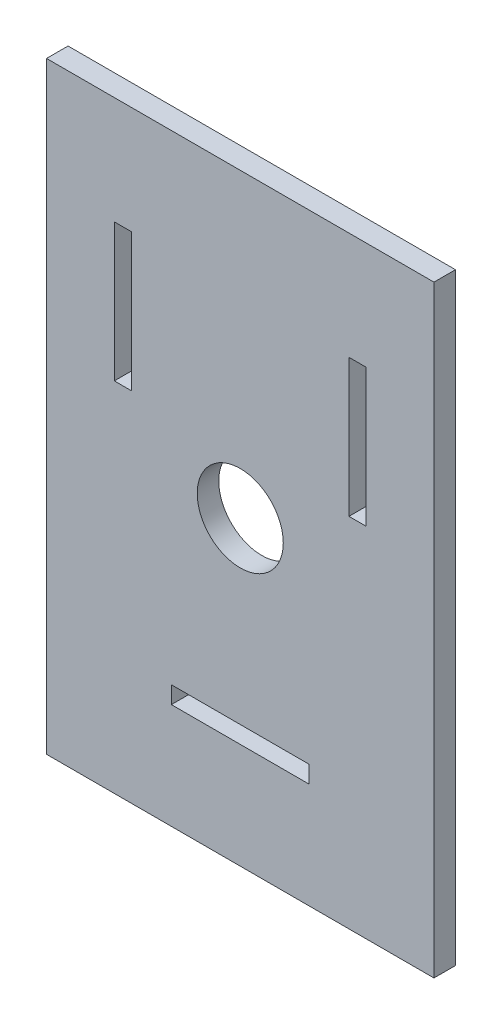
SolidWorks part; units mm, degrees
material "Alloy Steel"
ref_plane "Front Plane" through (0, 0, 0) normal (0, 0, 1) x (1, 0, 0)
ref_plane "Top Plane" through (0, 0, 0) normal (0, 1, 0) x (1, 0, 0)
ref_plane "Right Plane" through (0, 0, 0) normal (1, 0, 0) x (0, 0, -1)
sketch "BaseS" plane through (0, 0, 0) normal (0, 0, 1) x (1, 0, 0)
  line L1 (-9, 14) -> (9, 14)
  line L2 (-9, 14) -> (-9, -14)
  line L3 (-9, -14) -> (9, -14)
  line L4 (9, 14) -> (9, -14)
  line L5 (-9, 14) -> (9, -14) construction
  line L6 (-9, -14) -> (9, 14) construction
  point P0 (0, 0)
  dimension "Width" = 18
  dimension "Length" = 28
extrude "BASE" add sketch "BaseS" against normal blind 1
sketch "NeutralS" plane through (0, 0, 0) normal (0, 0, 1) x (1, 0, 0)
  line L1 (5.05, 9) -> (5.85, 9)
  line L2 (5.05, 9) -> (5.05, 2.6)
  line L3 (5.05, 2.6) -> (5.85, 2.6)
  line L4 (5.85, 9) -> (5.85, 2.6)
  line L5 (5.05, 9) -> (5.85, 2.6) construction
  line L6 (5.05, 2.6) -> (5.85, 9) construction
  point P0 (5.45, 5.8)
  dimension "Height" = 6.4
  dimension "Width" = 0.8
  dimension "XLoc" = 5.45
  dimension "YLoc" = 5.8
extrude "NEUTRAL" cut sketch "NeutralS" against normal blind 1.6
mirror "LINE HM" about plane through (0, 0, 0) normal (1, 0, 0) of "NEUTRAL"
sketch "ScrewAccessS" plane through (0, 0, 0) normal (0, 0, 1) x (1, 0, 0)
  circle A0 centre (0, 0) radius 2
  dimension "Dia" = 4
extrude "SCREW ACCESS" cut sketch "ScrewAccessS" against normal through all
sketch "GroundS" plane through (0, 0, 0) normal (0, 0, 1) x (1, 0, 0)
  line L0 (0, -8.7) -> (0, 0) construction
  line L1 (-3.2, -8.3) -> (3.2, -8.3)
  line L2 (-3.2, -8.3) -> (-3.2, -9.1)
  line L3 (-3.2, -9.1) -> (3.2, -9.1)
  line L4 (3.2, -8.3) -> (3.2, -9.1)
  line L5 (-3.2, -8.3) -> (3.2, -9.1) construction
  line L6 (-3.2, -9.1) -> (3.2, -8.3) construction
  point P0 (0, -8.7)
  dimension "GroundWidth" = 6.4
  dimension "D2" = 0.8
  dimension "YLoc" = 14.5
extrude "GROUND" cut sketch "GroundS" against normal blind 1.6
